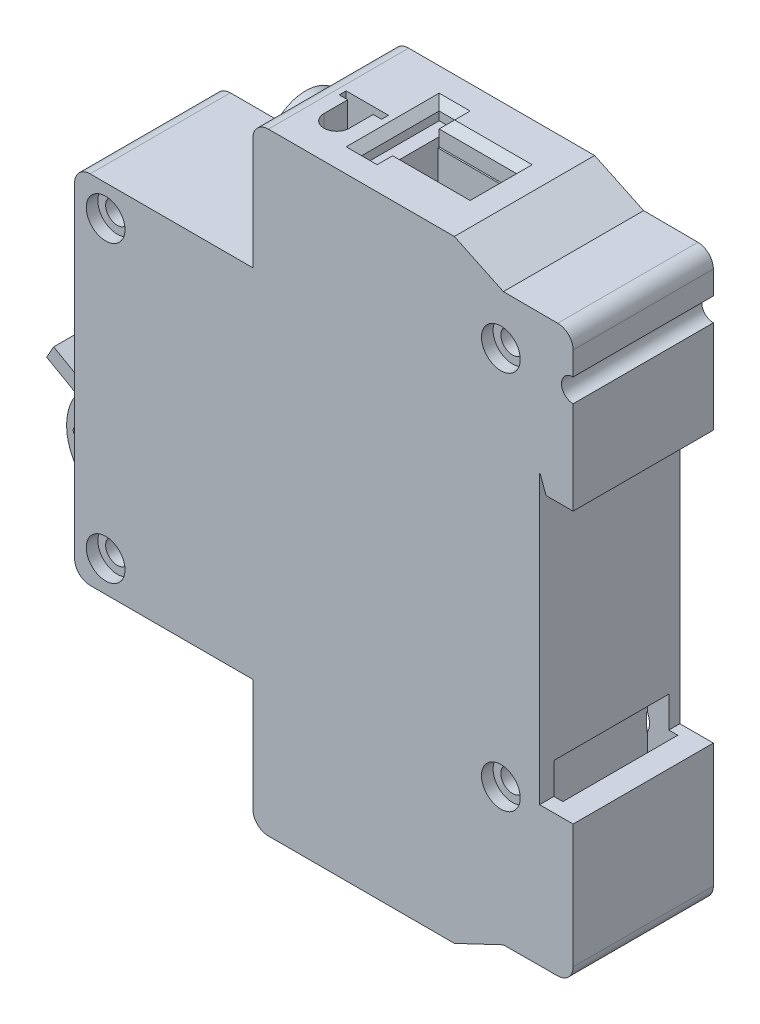
SolidWorks part; units mm, degrees
ref_plane "Front Plane" through (0, 0, 0) normal (0, 0, 1) x (1, 0, 0)
ref_plane "Top Plane" through (0, 0, 0) normal (0, 1, 0) x (1, 0, 0)
ref_plane "Right Plane" through (0, 0, 0) normal (1, 0, 0) x (0, 0, -1)
sketch "Sketch1" plane through (0, 0, 0) normal (0, 0, 1) x (1, 0, 0)
  line L0 (-34.1124, 21.4121) -> (25.8876, 21.4121) construction
  line L1 (-34.1124, 44.4121) -> (-11.1124, 44.4121)
  line L2 (-11.1124, 44.4121) -> (-11.1124, 60.9121)
  line L3 (30.2121, 57.8761) -> (30.2121, 52.8761)
  line L4 (30.2121, 49.8761) -> (30.2121, 37.8761)
  line L5 (30.2121, 37.8761) -> (26.7121, 37.8761)
  line L6 (25.9842, 39.9121) -> (25.8876, 39.9121)
  line L7 (-11.1124, 60.9121) -> (14.8876, 60.9121)
  line L8 (26.7121, 37.8761) -> (25.9842, 39.9121)
  line L9 (25.9842, 39.9121) -> (25.8876, 39.9121)
  line L10 (30.2121, 2.9121) -> (30.2121, -15.0519)
  line L11 (14.8876, 60.9121) -> (21.2122, 57.9121)
  line L12 (21.2122, 57.9121) -> (30.2121, 57.8761)
  line L13 (21.2122, -15.0879) -> (30.2121, -15.0519)
  line L14 (25.8876, 39.9121) -> (25.8876, 2.9121)
  line L15 (14.8876, -18.0879) -> (21.2122, -15.0879)
  line L16 (30.2121, 2.9121) -> (25.8876, 2.9121)
  line L22 (-11.1124, -18.0879) -> (14.8876, -18.0879)
  line L27 (-11.1124, -1.5879) -> (-11.1124, -18.0879)
  line L28 (-34.1124, -1.5879) -> (-11.1124, -1.5879)
  line L29 (-34.1124, 44.4121) -> (-34.1124, -1.5879)
  arc A0 (30.2121, 52.8761) -> (30.2121, 49.8761) centre (30.2121, 51.3761) ccw
  point P22 (25.8876, 21.4121)
  dimension "D11" = 3
  dimension "D1" = 23
  dimension "D2" = 23
  dimension "D3" = 16.5
  dimension "D4" = 16.5
  dimension "D5" = 9
  dimension "D6" = 7
  dimension "D7" = 20
  dimension "D8" = 73
  dimension "D9" = 3.5
  dimension "D13" = 60
  dimension "D14" = 46
  dimension "D15" = 46
  dimension "D16" = 5
  dimension "D17" = 37
  dimension "D18" = 26
  dimension "D19" = 26
extrude "Extrude1" add sketch "Sketch1" along normal blind 18.1 contours L29 L0 L14 L6 L8 L5 L4 A0 L3 L12 L11 L7 L2 L1 | L0 L29 L28 L27 L22 L15 L13 L10 L16 L14
sketch "Sketch3" plane through (0, 60.9121, 0) normal (0, 1, 0) x (1, 0, 0)
  line L0 (-11.1124, -18.1) -> (-11.1124, 0) construction
  line L1 (-1.1124, -4.0625) -> (0.8876, -4.0625)
  line L2 (-1.1124, -4.0625) -> (-1.1124, -14.0625)
  line L3 (-1.1124, -14.0625) -> (0.8876, -14.0625)
  line L4 (0.8876, -4.0625) -> (0.8876, -6.0625)
  line L5 (0.8876, -6.0625) -> (10.8876, -6.0625)
  line L6 (10.8876, -6.0625) -> (10.8876, -12.0625)
  line L7 (10.8876, -12.0625) -> (0.8876, -12.0625)
  line L8 (0.8876, -12.0625) -> (0.8876, -14.0625)
  dimension "D1" = 10
  dimension "D2" = 2
  dimension "D3" = 2
  dimension "D4" = 2
  dimension "D5" = 10
  dimension "D6" = 10
extrude "Cut-Extrude2" cut sketch "Sketch3" against normal through all
chamfer "Chamfer1" distance 1 angle 45 3 edges at (-0.1124, 60.9121, 14.0625) (-1.1124, 60.9121, 9.0625) (-0.1124, 60.9121, 4.0625)
chamfer "Chamfer5" distance 1 angle 45 1 edges at (5.8876, 60.9121, 12.0625)
chamfer "Chamfer6" distance 1 angle 45 9 edges at (0.8876, -18.0879, 13.0625) (5.8876, -18.0879, 12.0625) (10.8876, -18.0879, 9.0625) (5.8876, -18.0879, 6.0625) (0.8876, -18.0879, 5.0625) (0.8876, 60.9121, 14.0625) (0.8876, 60.9121, 4.5625) (5.8876, 60.9121, 6.0625) (10.8876, 60.9121, 9.5625)
sketch "Sketch5" plane through (-11.1124, 0, 0) normal (-1, 0, 0) x (0, 0, 1)
  circle A0 centre (8.75, -9.9617) radius 5.25
  circle A1 centre (8.7844, 53.0383) radius 5.25
  dimension "D1" = 63
  dimension "D2" = 10.5
  dimension "D3" = 10.5
extrude "Extrude4" add sketch "Sketch5" along normal blind 2.5
chamfer "Chamfer7" distance 1 angle 45 1 edges at (-1.1124, -18.0879, 9.0625)
chamfer "Chamfer8" distance 1 angle 45 2 edges at (-0.1124, -18.0879, 14.0625) (-0.1124, -18.0879, 4.0625)
sketch "Sketch16" plane through (-13.6124, 0, 0) normal (-1, 0, 0) x (0, 0, 1)
  circle A0 centre (8.75, -9.9617) radius 3.5
  circle A1 centre (8.7844, 53.0383) radius 3.5
  dimension "D1" = 7
  dimension "D2" = 7
extrude "Extrude5" cut sketch "Sketch16" against normal blind 14
sketch "Sketch17" plane through (-11.1124, 0, 0) normal (-1, 0, 0) x (0, 0, 1)
  line L2 (5.5892, 44.454) -> (11.9108, 44.454)
  line L3 (5.5892, 44.454) -> (5.5892, 46.9525)
  line L4 (5.5892, 46.9525) -> (11.9108, 46.9525)
  line L5 (11.9108, 44.454) -> (11.9108, 46.9525)
  line L6 (5.5892, 44.454) -> (11.9108, 46.9525) construction
  line L7 (11.3509, -3.9307) -> (5.781, -3.9307)
  line L8 (11.3509, -3.9307) -> (11.3509, -0.5824)
  line L9 (11.3509, -0.5824) -> (5.781, -0.5824)
  line L10 (5.781, -3.9307) -> (5.781, -0.5824)
  line L11 (11.3509, -3.9307) -> (5.781, -0.5824) construction
  line L12 (11.3509, -0.5824) -> (5.781, -3.9307) construction
  line L13 (5.5892, 46.9525) -> (11.9108, 44.454) construction
  point P0 (8.75, 45.7032)
  point P5 (8.5659, -2.2565)
extrude "Extrude6" add sketch "Sketch17" along normal blind 2
sketch "Sketch19" plane through (0, 0, 0) normal (0, 0, -1) x (-1, 0, 0)
  line L0 (34.1124, 44.4121) -> (34.1124, -1.5879) construction
  line L20 (34.1124, -1.5879) -> (34.1124, 44.4121)
  line L21 (34.1124, 44.4121) -> (11.1124, 44.4121)
  line L22 (11.1124, 44.4121) -> (11.1124, 60.9121)
  line L23 (11.1124, 60.9121) -> (-14.8876, 60.9121)
  line L24 (-14.8876, 60.9121) -> (-21.2122, 57.9121)
  line L25 (-21.2122, 57.9121) -> (-30.2121, 57.8761)
  line L26 (-30.2121, 57.8761) -> (-30.2121, 52.8761)
  line L27 (-30.2121, 49.8761) -> (-30.2121, 37.8761)
  line L28 (-30.2121, 37.8761) -> (-26.7121, 37.8761)
  line L29 (-26.7121, 37.8761) -> (-25.9842, 39.9121)
  line L30 (-25.9842, 39.9121) -> (-25.8876, 39.9121)
  line L31 (-25.8876, 39.9121) -> (-25.8876, 2.9121)
  line L32 (-25.8876, 2.9121) -> (-30.2121, 2.9121)
  line L33 (-30.2121, 2.9121) -> (-30.2121, -15.0519)
  line L34 (-30.2121, -15.0519) -> (-21.2122, -15.0879)
  line L35 (-21.2122, -15.0879) -> (-14.8876, -18.0879)
  line L36 (-14.8876, -18.0879) -> (11.1124, -18.0879)
  line L37 (11.1124, -18.0879) -> (11.1124, -1.5879)
  line L38 (11.1124, -1.5879) -> (34.1124, -1.5879)
  line L39 (34.1124, 7.025) -> (34.1124, 18.5894)
  arc A0 (34.1124, 7.025) -> (34.1124, 18.5894) centre (30.1302, 12.8072) ccw
  arc A2 (-30.2121, 49.8761) -> (-30.2121, 52.8761) centre (-30.2121, 51.3761) ccw
  dimension "D1" = 0
extrude "Extrude7" add sketch "Sketch19" against normal blind 2 from offset 2 separate body offset against normal yes
sketch "Sketch20" plane through (-34.1124, 0, 0) normal (-1, 0, 0) x (0, 0, 1)
  line L0 (9.05, -1.5879) -> (9.05, 44.4121) construction
  line L1 (18.1, -1.5879) -> (0, -1.5879) construction
  line L2 (18.1, 44.4121) -> (0, 44.4121) construction
sketch "Sketch21" plane through (0, 0, 18.1) normal (0, 0, 1) x (1, 0, 0)
  line L1 (-34.1124, 7.025) -> (-34.1124, 18.5894)
  line L2 (-34.1124, 7.025) -> (-34.1124, 18.5894)
  arc A0 (-34.1124, 7.025) -> (-34.1124, 18.5894) centre (-30.1302, 12.8072) cw
  arc A2 (-34.1124, 18.5894) -> (-34.1124, 7.025) centre (-30.1302, 12.8072) ccw
  dimension "D1" = 0
extrude "Extrude8" add sketch "Sketch21" against normal blind 2 from offset 2 separate body offset against normal yes
sketch "Sketch22" plane through (-34.1124, 0, 0) normal (-1, 0, 0) x (0, 0, 1)
  line L0 (9.05, -1.5879) -> (9.05, 44.4121) construction
  line L1 (13.7955, 6.8826) -> (4.3045, 6.8826)
  line L2 (13.7955, 6.8826) -> (13.7955, 18.812)
  line L3 (13.7955, 18.812) -> (4.3045, 18.812)
  line L4 (4.3045, 6.8826) -> (4.3045, 18.812)
  line L5 (13.7955, 6.8826) -> (4.3045, 18.812) construction
  line L6 (13.7955, 18.812) -> (4.3045, 6.8826) construction
  point P0 (9.05, 12.8473)
extrude "Extrude9" cut sketch "Sketch22" against normal blind 10
chamfer "Chamfer9" distance 1 angle 45 2 edges at (-34.1124, 6.8826, 9.05) (-34.1124, 18.812, 9.05)
fillet "Fillet2" radius 2 6 edges at (30.2121, -15.0519, 9.05) (30.2121, 57.8761, 9.05) (-11.1124, -18.0879, 9.05) (-34.1124, -1.5879, 9.05) (-11.1124, 60.9121, 9.05) (-34.1124, 44.4121, 9.05)
sketch "Sketch26" plane through (0.0608, -15.1726, 0) normal (0.004, -1, 0) x (1, 0.004, 0)
  line L1 (27.0559, 1.4217) -> (23.1228, 1.4217)
  line L2 (27.0559, 1.4217) -> (27.0559, 16.2526)
  line L3 (27.0559, 16.2526) -> (23.1228, 16.2526)
  line L4 (23.1228, 1.4217) -> (23.1228, 16.2526)
extrude "Extrude11" cut sketch "Sketch26" against normal blind 22
sketch "Sketch27" plane through (0, 0, 5.5892) normal (0, 0, -1) x (-1, 0, 0)
  circle A0 centre (12.1124, 45.7032) radius 0.5
  circle A1 centre (12.1124, -2.3691) radius 0.5
  dimension "D1" = 1
  dimension "D2" = 1
extrude "Extrude12" cut sketch "Sketch27" against normal through all
sketch "Sketch28" plane through (0, 0, 2) normal (0, 0, -1) x (-1, 0, 0)
  circle A0 centre (35.8027, 12.6705) radius 0.5
  dimension "D1" = 1
extrude "Extrude13" cut sketch "Sketch28" against normal through all
sketch "Sketch29" plane through (0, 0, 18.1) normal (0, 0, 1) x (1, 0, 0)
  line L0 (-30.1124, 44.4121) -> (-30.1124, -1.5879) construction
  line L1 (-32.1124, 44.4121) -> (-11.1124, 44.4121) construction
  line L2 (-32.1124, -1.5879) -> (-11.1124, -1.5879) construction
  line L3 (-34.1124, 40.4121) -> (22.422, 40.4121) construction
  line L4 (-34.1124, -1.5879) -> (-34.1124, 44.4121) construction
  line L5 (-34.1124, 2.4121) -> (21.6202, 2.4121) construction
  line L6 (20.8876, 57.1643) -> (20.8876, -4.4654) construction
  line L7 (12.3573, 51.9121) -> (25.6267, 51.9121) construction
  line L8 (25.8876, 39.9121) -> (25.8876, 2.9121) construction
  line L10 (-9.1124, 60.9121) -> (14.8876, 60.9121) construction
  circle A0 centre (-30.1124, 40.4121) radius 1.5
  circle A1 centre (20.8876, 51.4121) radius 1.5
  circle A2 centre (20.8876, 2.4121) radius 1.5
  circle A3 centre (-30.1124, 2.4121) radius 1.5
  dimension "D6" = 3
  dimension "D7" = 3
  dimension "D8" = 3
  dimension "D9" = 3
  dimension "D1" = 4
  dimension "D2" = 4
  dimension "D3" = 4
  dimension "D4" = 5
  dimension "D5" = 9
extrude "Extrude14" cut sketch "Sketch29" against normal through all
sketch "Sketch30" plane through (0, 0, 18.1) normal (0, 0, 1) x (1, 0, 0)
  circle A0 centre (-30.1124, 2.4121) radius 2.5
  circle A1 centre (-30.1124, 40.4121) radius 2.5
  circle A2 centre (20.8876, 2.4121) radius 2.5
  circle A3 centre (20.8876, 51.4121) radius 2.5
  dimension "D1" = 5
  dimension "D2" = 5
  dimension "D3" = 5
  dimension "D4" = 5
extrude "Extrude15" cut sketch "Sketch30" against normal blind 1.5
sketch "Sketch31" plane through (0, 0, 0) normal (0, 0, -1) x (-1, 0, 0)
  circle A0 centre (30.1124, 40.4121) radius 2.5
  circle A1 centre (30.1124, 2.4121) radius 2.5
  circle A2 centre (-20.8876, 51.4121) radius 2.5
  circle A3 centre (-20.8876, 2.4121) radius 2.5
  dimension "D1" = 5
  dimension "D2" = 5
  dimension "D3" = 5
  dimension "D4" = 5
extrude "Extrude16" cut sketch "Sketch31" against normal blind 1.5
sketch "Sketch32" plane through (0, 60.9121, 0) normal (0, 1, 0) x (1, 0, 0)
  line L0 (0.9435, -11.8039) -> (10.7693, -11.8039)
  line L1 (10.7693, -11.8039) -> (10.7693, -6.2677)
  line L2 (10.7693, -6.2677) -> (0.9435, -6.2677)
extrude "Extrude-Thin1" add sketch "Sketch32" against normal blind 72 from offset 3 thin offset against normal yes
sketch "Sketch33" plane through (0, 60.9121, 0) normal (0, 1, 0) x (1, 0, 0)
  line L1 (-1.0183, -4.1483) -> (0.762, -4.1483)
  line L2 (-1.0183, -4.1483) -> (-1.0183, -13.8958)
  line L3 (-1.0183, -13.8958) -> (0.762, -13.8958)
  line L4 (0.762, -4.1483) -> (0.762, -13.8958)
extrude "Extrude17" add sketch "Sketch33" against normal blind 74 from offset 2 separate body offset against normal yes
sketch "Sketch34" plane through (-1.0183, 0, 0) normal (-1, 0, 0) x (0, 0, 1)
  circle A0 centre (8.7844, 53.0383) radius 3.2642
  circle A1 centre (8.75, -9.9617) radius 3.1091
extrude "Extrude19" add sketch "Sketch34" along normal blind 10
sketch "Sketch35" plane through (-11.0183, 0, 0) normal (-1, 0, 0) x (0, 0, 1)
  line L0 (9.3034, -10.5872) -> (9.3034, -12.5447)
  line L1 (9.1664, 55.8914) -> (8.4024, 55.8914)
  line L2 (9.1664, 55.8914) -> (9.1664, 53.392)
  line L3 (9.1664, 50.1852) -> (8.4024, 50.1852)
  line L4 (8.4024, 55.8914) -> (8.4024, 53.392)
  line L5 (9.1664, 55.8914) -> (8.4024, 50.1852) construction
  line L6 (9.1664, 50.1852) -> (8.4024, 55.8914) construction
  line L7 (6.1428, 53.392) -> (8.4024, 53.392)
  line L8 (6.1428, 53.392) -> (6.1428, 52.6846)
  line L9 (6.1428, 52.6846) -> (8.4024, 52.6846)
  line L10 (11.4261, 53.392) -> (11.4261, 52.6846)
  line L11 (6.1428, 53.392) -> (11.4261, 52.6846) construction
  line L12 (6.1428, 52.6846) -> (11.4261, 53.392) construction
  line L13 (9.3034, -7.3787) -> (8.1966, -7.3787)
  line L14 (9.3034, -7.3787) -> (9.3034, -9.3362)
  line L15 (9.3034, -12.5447) -> (8.1966, -12.5447)
  line L16 (8.1966, -7.3787) -> (8.1966, -9.3362)
  line L17 (9.3034, -7.3787) -> (8.1966, -12.5447) construction
  line L18 (9.3034, -12.5447) -> (8.1966, -7.3787) construction
  line L19 (6.0739, -9.3362) -> (8.1966, -9.3362)
  line L20 (6.0739, -9.3362) -> (6.0739, -10.5872)
  line L21 (6.0739, -10.5872) -> (8.1966, -10.5872)
  line L22 (11.4261, -9.3362) -> (11.4261, -10.5872)
  line L23 (6.0739, -9.3362) -> (11.4261, -10.5872) construction
  line L24 (6.0739, -10.5872) -> (11.4261, -9.3362) construction
  line L25 (9.3034, -9.3362) -> (11.4261, -9.3362)
  line L26 (8.1966, -10.5872) -> (8.1966, -12.5447)
  line L27 (9.3034, -10.5872) -> (11.4261, -10.5872)
  line L28 (9.1664, 52.6846) -> (11.4261, 52.6846)
  line L29 (9.1664, 52.6846) -> (9.1664, 50.1852)
  line L30 (8.4024, 52.6846) -> (8.4024, 50.1852)
  line L31 (9.1664, 53.392) -> (11.4261, 53.392)
  point P0 (8.7844, 53.0383)
  point P6 (8.7844, 53.0383)
  point P11 (8.75, -9.9617)
  point P17 (8.75, -9.9617)
extrude "Extrude20" cut sketch "Sketch35" against normal blind 3
sketch "Sketch36" plane through (0, 0, 13.7955) normal (0, 0, -1) x (-1, 0, 0)
  circle A0 centre (28.9175, 12.6302) radius 6.1728
extrude "Extrude21" add sketch "Sketch36" along normal blind 9.2
sketch "Sketch37" plane through (0, 0, 16.1) normal (0, 0, 1) x (1, 0, 0)
  line L0 (-34.6439, 13.1129) -> (-41.7255, 17.1156)
  line L1 (-34.6439, 13.1129) -> (-33.7367, 14.7179)
  line L2 (-41.7255, 17.1156) -> (-40.8182, 18.7207)
  line L3 (-33.7367, 14.7179) -> (-40.8182, 18.7207)
extrude "Extrude22" add sketch "Sketch37" against normal blind 9 from offset 2 offset against normal yes
sketch "Sketch38" plane through (0, 60.9121, 0) normal (0, 1, 0) x (1, 0, 0)
  line L0 (-8.3628, -8.8104) -> (-2.9059, -8.8104)
  line L1 (-2.9059, -8.8104) -> (-2.9059, -9.705)
  line L2 (-2.9059, -9.705) -> (-3.9794, -9.705)
  line L3 (-3.9794, -9.705) -> (-3.9794, -12.7466)
  line L4 (-8.3628, -8.8104) -> (-8.3628, -9.705)
  line L5 (-8.3628, -9.705) -> (-7.2638, -9.705)
  line L6 (-7.2638, -9.705) -> (-7.2638, -12.7466)
  arc A0 (-7.2638, -12.7466) -> (-3.9794, -12.7466) centre (-5.6216, -12.7767) ccw
extrude "Extrude23" cut sketch "Sketch38" against normal blind 8
sketch "Sketch39" plane through (0, 44.4121, 0) normal (0, 1, 0) x (-1, 0, 0)
  line L0 (-0.762, 13.8958) -> (-0.762, 4.1483) construction
  line L1 (-0.762, 6.3337) -> (-10.7693, 6.3337)
  line L2 (-0.762, 6.3337) -> (-0.762, 11.8039)
  line L3 (-0.762, 11.8039) -> (-10.7693, 11.8039)
  line L4 (-10.7693, 6.3337) -> (-10.7693, 11.8039)
  line L5 (-0.9435, 11.8039) -> (-10.7693, 11.8039) construction
extrude "Extrude24" add sketch "Sketch39" along normal blind 10 from offset 30 offset against normal yes
